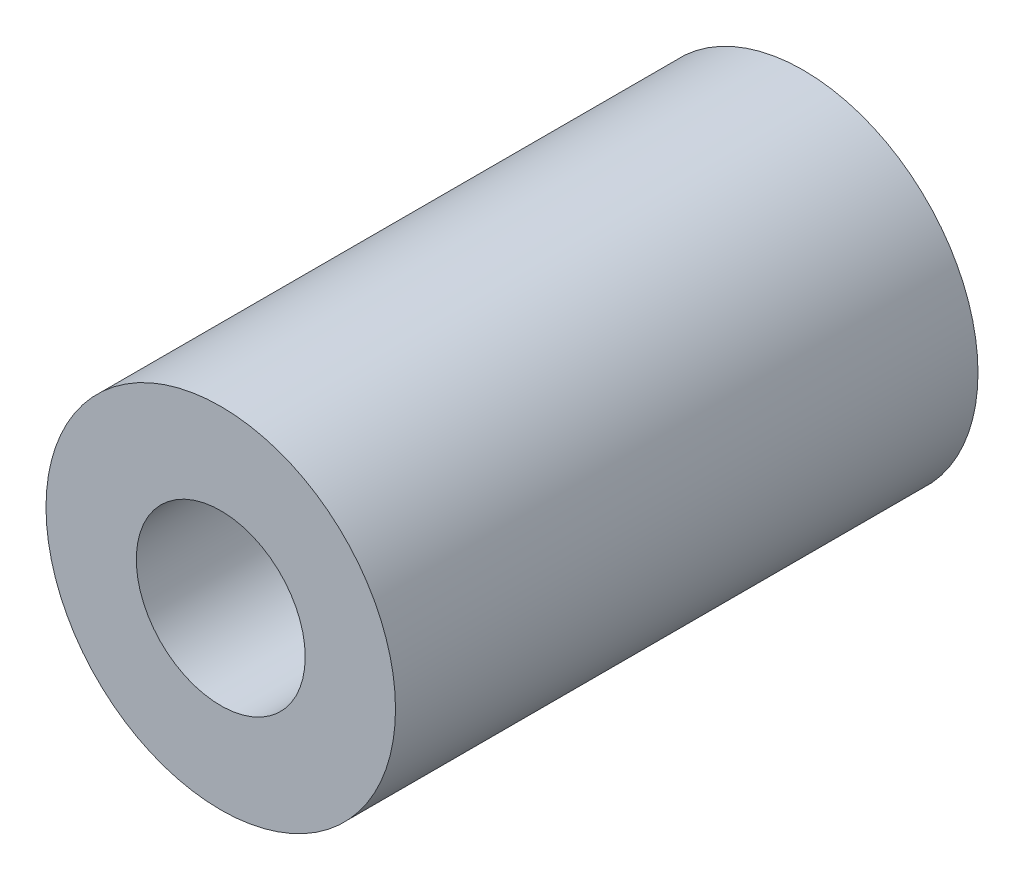
SolidWorks part; units mm, degrees
material "1.4003 (X2CrNi12)"
ref_plane "Ön Düzlem" through (0, 0, 0) normal (0, 0, 1) x (1, 0, 0)
ref_plane "Üst Düzlem" through (0, 0, 0) normal (0, 1, 0) x (1, 0, 0)
ref_plane "Sağ Düzlem" through (0, 0, 0) normal (1, 0, 0) x (0, 0, -1)
sketch "Çizim1" plane through (0, 0, 0) normal (0, 0, 1) x (1, 0, 0)
  circle A0 centre (0, 0) radius 15
  circle A1 centre (0, 0) radius 7.25
  dimension "D1" = 14.5
  dimension "D2" = 30
extrude "Yükseklik-Ekstrüzyon1" add sketch "Çizim1" along normal blind 50
cosmetic thread "Kozmetik Diş Açma1" parameters "D2"=16
